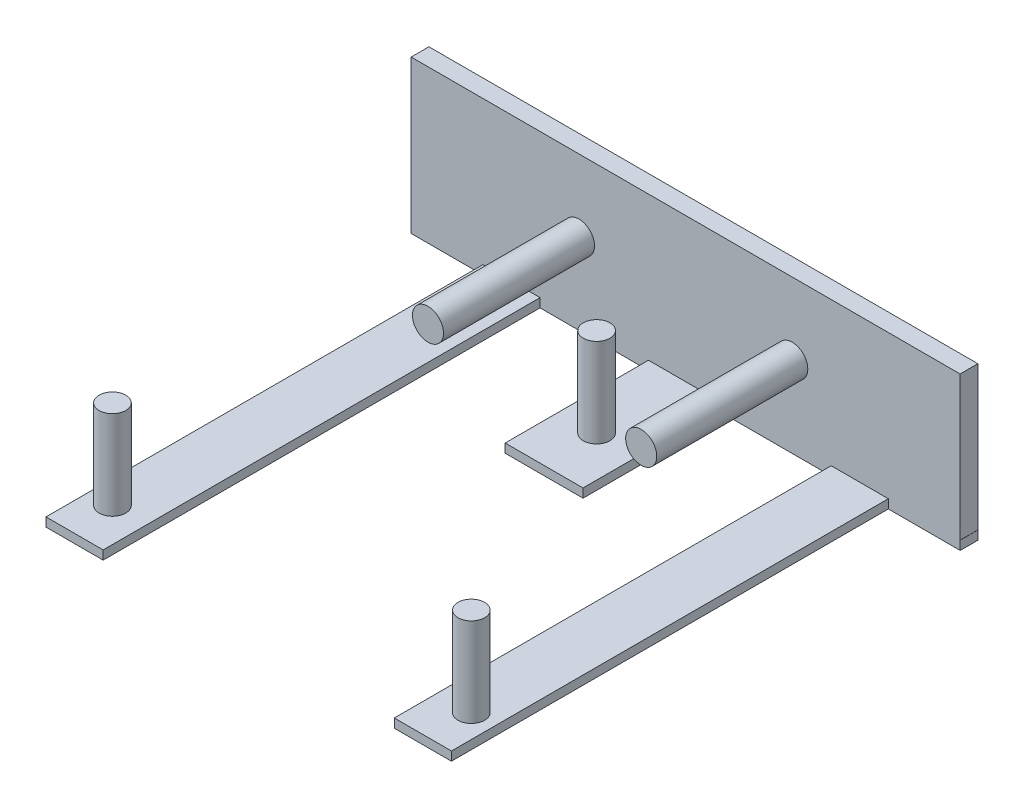
SolidWorks part; units mm, degrees
ref_plane "Front Plane" through (0, 0, 0) normal (0, 0, 1) x (1, 0, 0)
ref_plane "Top Plane" through (0, 0, 0) normal (0, 1, 0) x (1, 0, 0)
ref_plane "Right Plane" through (0, 0, 0) normal (1, 0, 0) x (0, 0, -1)
sketch "Sketch1" plane through (0, 0, 0) normal (0, 0, 1) x (1, 0, 0)
  circle A0 centre (29.9691, 8.382) radius 4.445
extrude "Boss-Extrude1" add sketch "Sketch1" against normal blind 43.18 from offset 5.08
ref_plane "Plane1" through (-0.5109, 0, 0) normal (1, 0, 0) x (0, 0, -1)
mirror "Mirror2" about plane through (-0.5109, 0, 0) normal (1, 0, 0) of bodies 101
ref_plane "Plane2" through (0, -12.192, 0) normal (0, -1, 0) x (-1, 0, 0)
sketch "Sketch2" plane through (0, 0, -38.1) normal (0, 0, -1) x (-1, 0, 0)
  line L0 (-29.9691, 8.382) -> (30.9909, 8.382) construction
  line L2 (-77.9541, -12.192) -> (78.9758, -12.192)
  line L3 (-77.9541, -12.192) -> (-77.9541, 28.956)
  line L4 (-77.9541, 28.956) -> (78.9758, 28.956)
  line L5 (78.9758, -12.192) -> (78.9758, 28.956)
  line L6 (-77.9541, -12.192) -> (78.9758, 28.956) construction
  line L7 (-77.9541, 28.956) -> (78.9758, -12.192) construction
  line L8 (-92.7428, -12.192) -> (92.7428, -12.192) construction
  point P4 (0.5109, 8.382)
extrude "Boss-Extrude2" add sketch "Sketch2" along normal blind 5.08
sketch "Sketch3" plane through (0, -12.192, 0) normal (0, -1, 0) x (1, 0, 0)
  line L0 (-11.1297, -43.18) -> (11.1297, -43.18)
  line L1 (77.9541, -43.18) -> (-78.9758, -43.18) construction
  line L3 (-11.1297, -43.18) -> (-11.1297, 2.8726)
  line L4 (11.1297, -43.18) -> (11.1297, 2.8726)
  line L5 (-11.1297, 2.8726) -> (11.1297, 2.8726)
  point P5 (0, -43.18)
extrude "Boss-Extrude3" add sketch "Sketch3" along normal blind 2.54
sketch "Sketch4" plane through (0, -12.192, 0) normal (0, -1, 0) x (-1, 0, 0)
  line L0 (50.2956, -75.34) -> (50.2956, 43.18) construction
  line L1 (11.1297, 43.18) -> (78.9758, 43.18) construction
  line L2 (42.1262, 43.18) -> (58.465, 43.18)
  line L3 (58.465, 43.18) -> (58.465, -86.8039)
  line L4 (42.1262, 43.18) -> (42.1262, -86.8039)
  line L5 (42.1262, -86.8039) -> (58.465, -86.8039)
  point P7 (50.2956, 43.18)
extrude "Boss-Extrude4" add sketch "Sketch4" along normal blind 2.54
mirror "Mirror3" about plane through (-0.5109, 0, 0) normal (1, 0, 0) of "Boss-Extrude4"
sketch "Sketch5" plane through (0, -12.192, 0) normal (0, -1, 0) x (1, 0, 0)
  line L0 (-78.9758, -43.18) -> (-78.9758, -38.1)
  line L1 (-78.9758, -43.18) -> (77.9955, -43.18)
  line L2 (-78.9758, -38.1) -> (77.9955, -38.1)
  line L3 (77.9955, -43.18) -> (77.9955, -38.1)
extrude "Boss-Extrude5" add sketch "Sketch5" along normal up to surface (2.54 mm away) up to face at (49.2739, -14.732, 21.8119)
sketch "Sketch6" plane through (0, -12.192, 0) normal (0, 1, 0) x (1, 0, 0)
  circle A0 centre (-0.5109, 12.6433) radius 3.81
extrude "Boss-Extrude6" add sketch "Sketch6" along normal blind 25.4
ref_plane "Plane3" through (57.4433, -12.192, -38.1) normal (0, 0, -1) x (-1, 0, 0)
sketch "Sketch8" plane through (0, -12.192, 0) normal (0, 1, 0) x (1, 0, 0)
  circle A0 centre (50.7926, -74.4632) radius 3.81
extrude "Boss-Extrude7" add sketch "Sketch8" along normal blind 25.4
mirror "Mirror4" about plane through (-0.5109, 0, 0) normal (1, 0, 0) of "Boss-Extrude7"
